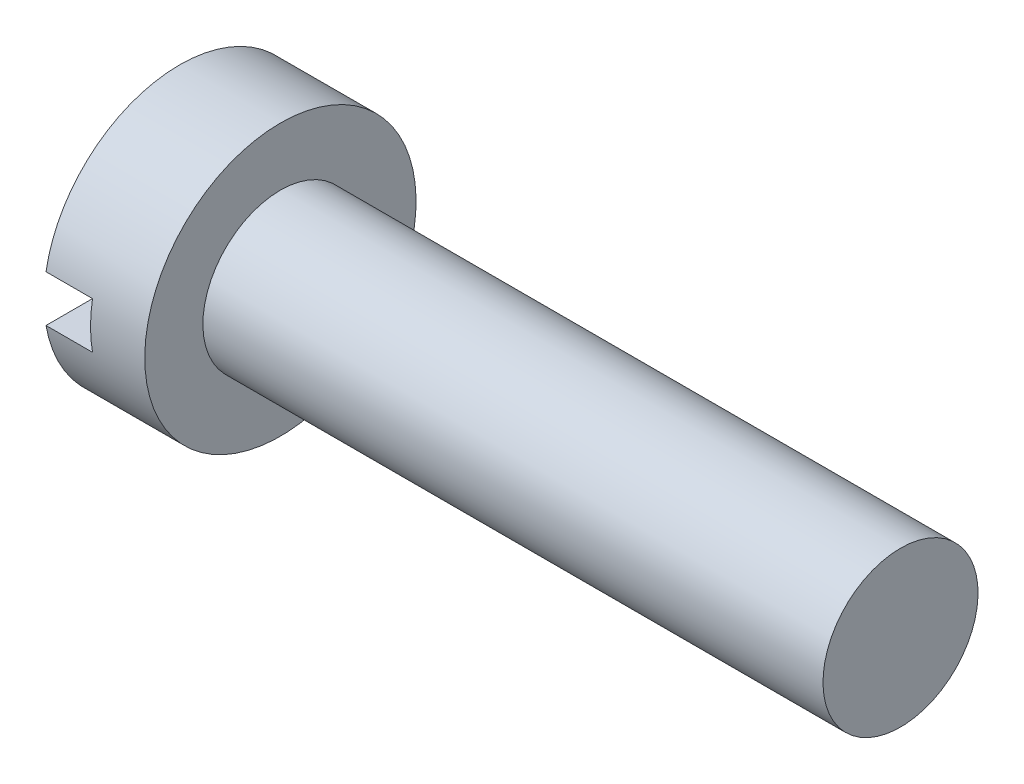
SolidWorks part; units mm, degrees
material "Plain Carbon Steel"
ref_plane "Front Plane" through (0, 0, 0) normal (0, 0, 1) x (1, 0, 0)
ref_plane "Top Plane" through (0, 0, 0) normal (0, 1, 0) x (1, 0, 0)
ref_plane "Right Plane" through (0, 0, 0) normal (1, 0, 0) x (0, 0, -1)
sketch "Sketch1" plane through (0, 0, 0) normal (0, 0, 1) x (1, 0, 0)
  line L0 (0, 0) -> (0, 3.5)
  line L1 (0, 3.5) -> (2.6, 3.5)
  line L2 (2.6, 3.5) -> (2.6, 2)
  line L3 (2.6, 2) -> (18.6, 2)
  line L4 (18.6, 2) -> (18.6, 0)
  line L5 (18.6, 0) -> (0, 0) construction
  line L6 (0, 0) -> (18.6, 0)
  dimension "D1" = 4
  dimension "D2" = 16
  dimension "D3" = 7
  dimension "D4" = 2.6
revolve "Revolve1" add sketch "Sketch1" angle 360 about L5
sketch "Sketch2" plane through (0, 0, 0) normal (-1, 0, 0) x (0, 0, 1)
  line L0 (3.5, 0) -> (-3.5, 0) construction
  line L1 (-3.5, 0.6) -> (3.5, 0.6)
  line L2 (-3.5, 0.6) -> (-3.5, -0.6)
  line L3 (-3.5, -0.6) -> (3.5, -0.6)
  line L4 (3.5, 0.6) -> (3.5, -0.6)
  circle A0 centre (0, 0) radius 3.5 construction
  dimension "D1" = 1.2
extrude "Cut-Extrude1" cut sketch "Sketch2" against normal blind 1.2
